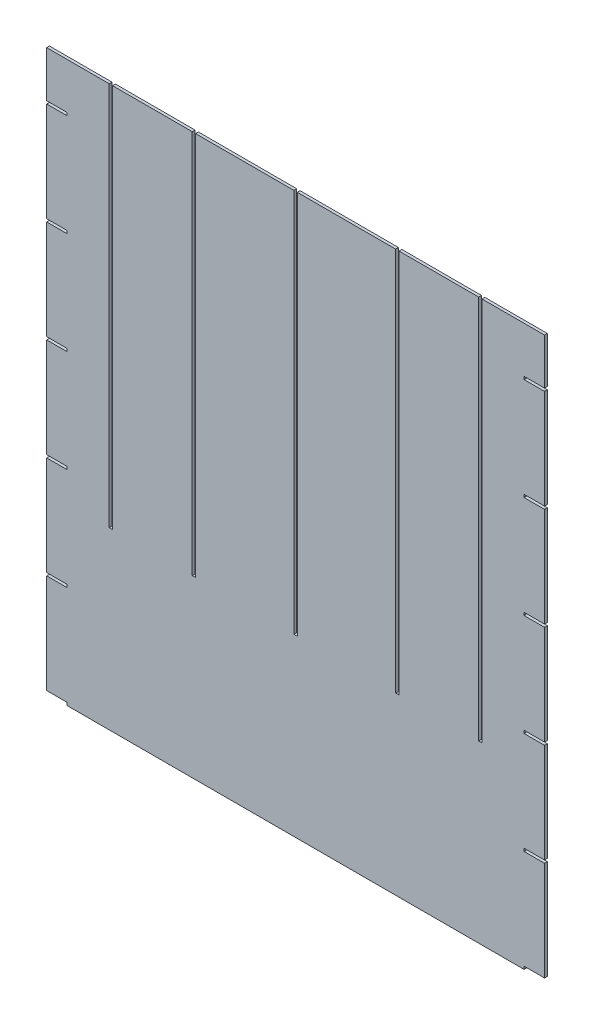
SolidWorks part; units mm, degrees
ref_plane "Front Plane" through (0, 0, 0) normal (0, 0, 1) x (1, 0, 0)
ref_plane "Top Plane" through (0, 0, 0) normal (0, 1, 0) x (1, 0, 0)
ref_plane "Right Plane" through (0, 0, 0) normal (1, 0, 0) x (0, 0, -1)
sketch "Model" plane through (0, 0, 0) normal (0, 0, 1) x (1, 0, 0)
  line L0 (-268.0037, 3) -> (-245.9797, 3)
  line L1 (-245.9797, 3) -> (-245.9797, 0)
  line L2 (245.9797, 0) -> (-245.9797, 0)
  line L3 (245.9797, 0) -> (245.9797, 3)
  line L4 (268.0037, 3) -> (245.9797, 3)
  line L5 (268.0037, 3) -> (268.0037, 110)
  line L6 (268.0037, 110) -> (245.9797, 110)
  line L7 (245.9797, 113) -> (245.9797, 110)
  line L8 (268.0037, 113) -> (245.9797, 113)
  line L9 (268.0037, 113) -> (268.0037, 220)
  line L10 (268.0037, 220) -> (245.9797, 220)
  line L11 (245.9797, 223) -> (245.9797, 220)
  line L12 (268.0037, 223) -> (245.9797, 223)
  line L13 (268.0037, 223) -> (268.0037, 330)
  line L14 (268.0037, 330) -> (245.9797, 330)
  line L15 (245.9797, 333) -> (245.9797, 330)
  line L16 (268.0037, 333) -> (245.9797, 333)
  line L17 (268.0037, 333) -> (268.0037, 440)
  line L18 (268.0037, 440) -> (245.9797, 440)
  line L19 (245.9797, 443) -> (245.9797, 440)
  line L20 (268.0037, 443) -> (245.9797, 443)
  line L21 (268.0037, 443) -> (268.0037, 550)
  line L22 (268.0037, 550) -> (245.9797, 550)
  line L23 (245.9797, 550) -> (245.9797, 553)
  line L24 (268.0037, 553) -> (245.9797, 553)
  line L25 (268.0037, 553) -> (268.0037, 602.5348)
  line L26 (200.7227, 602.5348) -> (268.0037, 602.5348)
  line L27 (200.7227, 602.5348) -> (200.7227, 188.6103)
  line L28 (200.7227, 188.6103) -> (197.1227, 188.6103)
  line L29 (197.1227, 188.6103) -> (197.1227, 602.5348)
  line L30 (111.3, 602.5348) -> (197.1227, 602.5348)
  line L31 (111.3, 602.5348) -> (111.3, 188.6103)
  line L32 (111.3, 188.6103) -> (107.7, 188.6103)
  line L33 (107.7, 188.6103) -> (107.7, 602.5348)
  line L34 (1.8, 602.5348) -> (107.7, 602.5348)
  line L35 (1.8, 602.5348) -> (1.8, 188.6103)
  line L36 (1.8, 188.6103) -> (-1.8, 188.6103)
  line L37 (-1.8, 188.6103) -> (-1.8, 602.5348)
  line L38 (-107.7, 602.5348) -> (-1.8, 602.5348)
  line L39 (-107.7, 602.5348) -> (-107.7, 188.6103)
  line L40 (-107.7, 188.6103) -> (-111.3, 188.6103)
  line L41 (-111.3, 188.6103) -> (-111.3, 602.5348)
  line L42 (-197.1227, 602.5348) -> (-111.3, 602.5348)
  line L43 (-197.1227, 602.5348) -> (-197.1227, 188.6103)
  line L44 (-197.1227, 188.6103) -> (-200.7227, 188.6103)
  line L45 (-200.7227, 188.6103) -> (-200.7227, 602.5348)
  line L46 (-268.0037, 602.5348) -> (-200.7227, 602.5348)
  line L47 (-268.0037, 553) -> (-268.0037, 602.5348)
  line L48 (-268.0037, 553) -> (-245.9797, 553)
  line L49 (-245.9797, 550) -> (-245.9797, 553)
  line L50 (-268.0037, 550) -> (-245.9797, 550)
  line L51 (-268.0037, 443) -> (-268.0037, 550)
  line L52 (-268.0037, 443) -> (-245.9797, 443)
  line L53 (-245.9797, 440) -> (-245.9797, 443)
  line L54 (-268.0037, 440) -> (-245.9797, 440)
  line L55 (-268.0037, 333) -> (-268.0037, 440)
  line L56 (-268.0037, 333) -> (-245.9797, 333)
  line L57 (-245.9797, 333) -> (-245.9797, 330)
  line L58 (-268.0037, 330) -> (-245.9797, 330)
  line L59 (-268.0037, 223) -> (-268.0037, 330)
  line L60 (-268.0037, 223) -> (-245.9797, 223)
  line L61 (-245.9797, 223) -> (-245.9797, 220)
  line L62 (-268.0037, 220) -> (-245.9797, 220)
  line L63 (-268.0037, 113) -> (-268.0037, 220)
  line L64 (-268.0037, 113) -> (-245.9797, 113)
  line L65 (-245.9797, 113) -> (-245.9797, 110)
  line L66 (-268.0037, 110) -> (-245.9797, 110)
  line L67 (-268.0037, 3) -> (-268.0037, 110)
extrude "Boss-Extrude1" add sketch "Model" along normal blind 3
